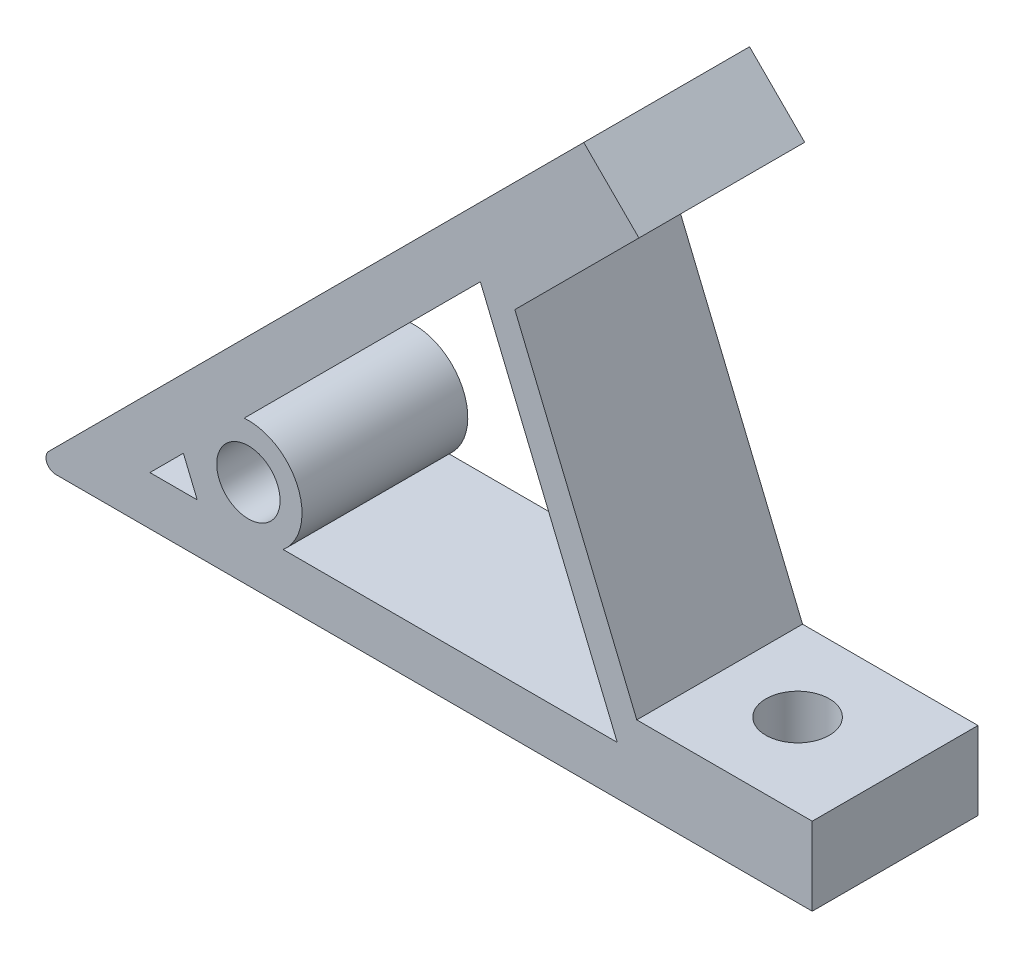
SolidWorks part; units mm, degrees
ref_plane "前视基准面" through (0, 0, 0) normal (0, 0, 1) x (1, 0, 0)
ref_plane "上视基准面" through (0, 0, 0) normal (0, 1, 0) x (1, 0, 0)
ref_plane "右视基准面" through (0, 0, 0) normal (1, 0, 0) x (0, 0, -1)
sketch "草图1" plane through (0, 0, 0) normal (0, 0, 1) x (1, 0, 0)
  line B0 (-77.5858, 0) -> (0, 0)
  line B1 (-67.9289, 5) -> (-63.0745, 5)
  line B2 (-54.2575, 5) -> (-20, 5)
  line B3 (-17.9955, 8) -> (0, 8)
  line B4 (-78.2929, 1.7071) -> (-23.4315, 56.5685)
  line B5 (-67.9289, 5) -> (-64.4963, 8.4326)
  line B6 (-58.2617, 14.6672) -> (-34.0381, 38.8909)
  line B7 (-30.4993, 38.187) -> (-17.7746, 50.9117)
  line B8 (0, 0) -> (0, 8)
  line B9 (-17.7746, 50.9117) -> (-23.4315, 56.5685)
  line B10 (-20, 5) -> (-34.0381, 38.8909)
  line B11 (-17.9955, 8) -> (-30.4993, 38.187)
  line B12 (-63.0745, 5) -> (-64.4963, 8.4326)
  arc B13 (-78.2929, 1.7071) -> (-77.5858, 0) centre (-77.5858, 1) ccw
  circle B14 centre (-57.8269, 9.1844) radius 3.25
  arc B15 (-54.2575, 5) -> (-58.2617, 14.6672) centre (-57.8269, 9.1844) ccw
sketch_block_instance "A$C18907C9D-1"
sketch_block "A$C18907C9D"
extrude "凸台-拉伸1" add sketch "草图1" along normal mid plane 17
sketch "草图3" plane through (0, 8, 0) normal (0, 1, 0) x (1, 0, 0)
  line L0 (0, -8.5) -> (0, 8.5) construction
  circle A0 centre (-10, 0) radius 3.25
  dimension "D1" = 10
extrude "切除-拉伸1" cut sketch "草图3" against normal blind 17
sketch "草图4" plane through (-12.5317, -5.1908, 0) normal (0.9239, 0.3827, 0) x (0, 0, -1)
  line L0 (-8.5, 30.6147) -> (8.5, 30.6147) construction
  line L1 (-8.5, 14.2776) -> (-8.5, 46.9517) construction
  line L2 (8.5, 14.2776) -> (8.5, 46.9517) construction
ref_plane "基准面2" through (-11.7157, 28.2843, 0) normal (-0.3827, 0.9239, 0) x (0.9239, 0.3827, 0)
mirror "镜向1" about plane through (-11.7157, 28.2843, 0) normal (-0.3827, 0.9239, 0) of "切除-拉伸1"
